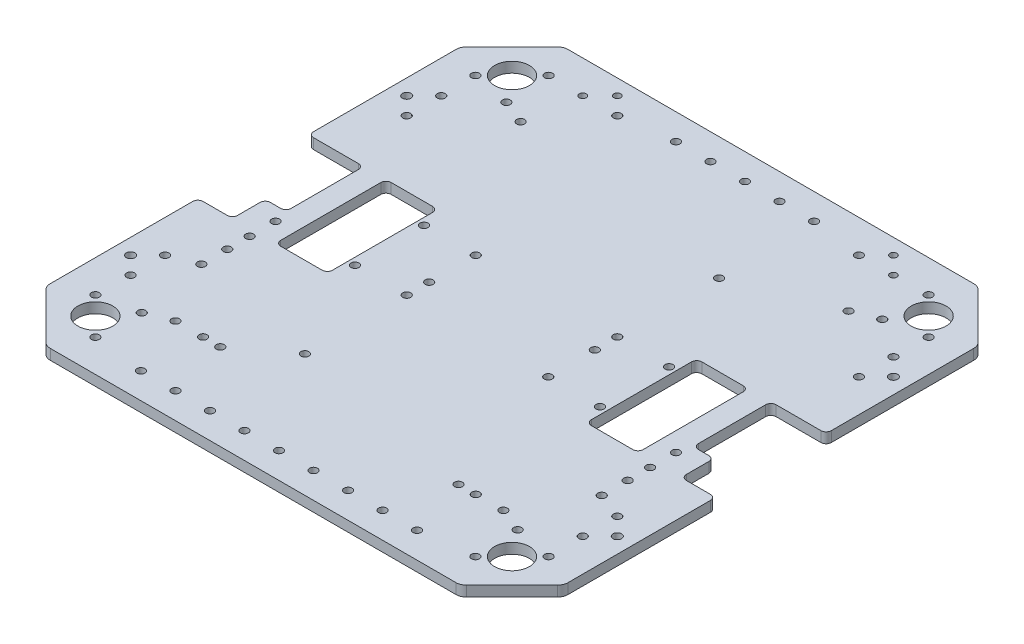
SolidWorks part; units mm, degrees
ref_plane "Plan de face" through (0, 0, 0) normal (0, 0, 1) x (1, 0, 0)
ref_plane "Plan de dessus" through (0, 0, 0) normal (0, 1, 0) x (1, 0, 0)
ref_plane "Plan de droite" through (0, 0, 0) normal (1, 0, 0) x (0, 0, -1)
sketch "Esquisse1" plane through (0, 0, 0) normal (0, 1, 0) x (1, 0, 0)
  line L0 (150, -150) -> (150, 150) construction
  line L1 (150, 150) -> (0, 150) construction
  line L2 (-150, 150) -> (-150, -150) construction
  line L3 (-150, 150) -> (150, 150) construction
  line L4 (150, 0) -> (-150, 0) construction
  line L5 (150, -150) -> (-150, -150) construction
  line L6 (0, 150) -> (0, -150) construction
  line L7 (-150, 0) -> (-150, 120)
  line L8 (0, 150) -> (-120, 150)
  line L9 (-150, 120) -> (-120, 150)
  line L10 (0, 150) -> (120, 150)
  line L11 (150, 0) -> (150, 120)
  line L12 (150, 120) -> (120, 150)
  line L13 (-150, 0) -> (-150, -120)
  line L14 (0, -150) -> (-120, -150)
  line L15 (-120, -150) -> (-150, -120)
  line L16 (150, 0) -> (150, -120)
  line L17 (0, -150) -> (120, -150)
  line L18 (120, -150) -> (150, -120)
  dimension "D1" = 42.4264
  dimension "D2" = 240
  dimension "D3" = 120
  dimension "D4" = 42.4264
  dimension "D5" = 120
  dimension "D6" = 300
  dimension "D7" = 300
  dimension "D8" = 30
extrude "Boss.-Extru.1" add sketch "Esquisse1" along normal blind 6
sketch "Esquisse2" plane through (0, 6, 0) normal (0, 1, 0) x (1, 0, 0)
  line L0 (-150, 0) -> (150, 0) construction
  line L1 (-150, 120) -> (-150, -120) construction
  line L2 (150, -120) -> (150, 120) construction
  line L3 (0, -150) -> (0, 150) construction
  line L4 (-120, -150) -> (120, -150) construction
  line L5 (120, 150) -> (-120, 150) construction
  line L6 (-150, 120) -> (-120, 150) construction
  line L7 (-120, 150) -> (-105.6975, 135.6975) construction
  line L8 (-105.6975, 135.6975) -> (-135.6975, 105.6975) construction
  line L9 (-135.6975, 105.6975) -> (-150, 120) construction
  line L10 (-120.6975, 120.6975) -> (-110.0909, 131.3041) construction
  line L11 (-120.6975, 120.6975) -> (-131.3041, 110.0909) construction
  line L12 (-135, -135) -> (135, 135) construction
  line L13 (-150, -120) -> (-120, -150) construction
  line L14 (150, 120) -> (120, 150) construction
  line L15 (-120.6975, 120.6975) -> (0, 120.6975) construction
  circle A0 centre (-120.6975, 120.6975) radius 10.1
  circle A1 centre (-131.3041, 110.0909) radius 2.3
  circle A2 centre (-110.0909, 131.3041) radius 2.3
extrude "Enlèv. mat.-Extru.1" cut sketch "Esquisse2" against normal up to next
mirror "Symétrie1" about plane through (0, 0, 0) normal (1, 0, 0) of "Enlèv. mat.-Extru.1"
mirror "Symétrie2" about plane through (0, 0, 0) normal (0, 0, 1) of "Symétrie1", "Enlèv. mat.-Extru.1"
sketch "Esquisse3" plane through (0, 6, 0) normal (0, 1, 0) x (1, 0, 0)
  line L0 (-150, 0) -> (150, 0) construction
  line L1 (-150, 120) -> (-150, -120) construction
  line L2 (150, -120) -> (150, 120) construction
  line L3 (0, -150) -> (0, 150) construction
  line L4 (-120, -150) -> (120, -150) construction
  line L5 (120, 150) -> (-120, 150) construction
  line L6 (-150, 0) -> (-150, -32)
  line L7 (-150, -32) -> (-130, -32)
  line L8 (-130, -32) -> (-130, 32)
  line L9 (-130, 32) -> (-150, 32)
  line L10 (-150, 32) -> (-150, 0)
extrude "Enlèv. mat.-Extru.2" cut sketch "Esquisse3" against normal up to next and the other way through all
mirror "Symétrie3" about plane through (0, 0, 0) normal (1, 0, 0) of "Enlèv. mat.-Extru.2"
fillet "Congé1" radius 3 8 edges at (-150, 3, 32) (-130, 3, 32) (-150, 3, -32) (-130, 3, -32) (150, 3, -32) (130, 3, -32) (150, 3, 32) (130, 3, 32)
sketch "Esquisse4" plane through (0, 6, 0) normal (0, 1, 0) x (1, 0, 0)
  line L0 (0, -150) -> (0, 150) construction
  line L1 (-120, -150) -> (120, -150) construction
  line L2 (120, 150) -> (-120, 150) construction
  line L3 (0, 150) -> (0, 0) construction
  line L4 (0, 0) -> (-130, 0) construction
  line L5 (-130, -29) -> (-130, 29) construction
  line L6 (-130, 0) -> (-105, 0) construction
  line L7 (-105, 0) -> (-105, 32)
  line L8 (-105, 32) -> (-75, 32)
  line L9 (-75, 32) -> (-75, -32)
  line L10 (-75, -32) -> (-105, -32)
  line L11 (-105, -32) -> (-105, 0)
extrude "Enlèv. mat.-Extru.3" cut sketch "Esquisse4" against normal up to next
mirror "Symétrie4" about plane through (0, 0, 0) normal (1, 0, 0) of "Enlèv. mat.-Extru.3"
fillet "Congé2" radius 3 8 edges at (105, 3, -32) (75, 3, -32) (105, 3, 32) (75, 3, 32) (-105, 3, 32) (-75, 3, 32) (-75, 3, -32) (-105, 3, -32)
sketch "Esquisse5" plane through (0, 6, 0) normal (0, 1, 0) x (1, 0, 0)
  line L0 (-75, 0) -> (-67, 0) construction
  line L1 (-75, -29) -> (-75, 29) construction
  line L2 (-67, 0) -> (-67, 24) construction
  line L3 (-67, 0) -> (-67, -24) construction
  line L4 (-67, -24) -> (-75, -24) construction
  line L5 (-75, -24) -> (-75, -16) construction
  line L6 (-75, -16) -> (-67, -24) construction
  line L7 (-67, -24) -> (-75, -24) construction
  line L9 (-67, 24) -> (-75, 24) construction
  line L10 (-75, 24) -> (-75, 16) construction
  line L11 (-75, 16) -> (-67, 24) construction
  line L12 (-67, 24) -> (-75, 24) construction
  circle A0 centre (-71, 20) radius 2.3
  circle A1 centre (-71, -20) radius 2.3
extrude "Enlèv. mat.-Extru.4" cut sketch "Esquisse5" against normal up to next
mirror "Symétrie5" about plane through (0, 0, 0) normal (1, 0, 0) of "Enlèv. mat.-Extru.4"
sketch "Esquisse6" plane through (0, 6, 0) normal (0, 1, 0) x (1, 0, 0)
  line L0 (-75, 0) -> (-75, 24) construction
  line L1 (-75, -29) -> (-75, 29) construction
  line L2 (-75, 24) -> (-67, 24) construction
  line L3 (-67, 24) -> (-45, 24) construction
  line L4 (-45, 24) -> (-37, 24) construction
  line L5 (-37, 24) -> (-37, -24) construction
  line L6 (-37, -24) -> (-45, -24) construction
  line L7 (-45, 24) -> (-45, 16) construction
  line L8 (-45, 16) -> (-37, 24) construction
  line L9 (-45, -24) -> (-45, -16) construction
  line L10 (-45, -16) -> (-37, -24) construction
  line L11 (-37, 24) -> (-37, -83) construction
  line L12 (-37, -83) -> (-45, -83) construction
  line L13 (-45, -83) -> (-45, -75) construction
  line L14 (-45, -75) -> (-37, -83) construction
  line L15 (75, 0) -> (67, 0) construction
  line L16 (75, -29) -> (75, 29) construction
  line L17 (75, 0) -> (75, -24) construction
  line L18 (75, -24) -> (67, -24) construction
  line L19 (67, 24) -> (75, 24) construction
  line L20 (75, 24) -> (75, 0) construction
  line L21 (67, -24) -> (45, -24) construction
  line L22 (45, -24) -> (45, -16) construction
  line L23 (67, -24) -> (67, 0) construction
  line L24 (45, -16) -> (37, -16) construction
  line L25 (37, -16) -> (37, -24) construction
  line L26 (37, -24) -> (45, -24) construction
  line L27 (45, -24) -> (37, -16) construction
  line L28 (37, -24) -> (37, 83) construction
  line L29 (37, 83) -> (45, 83) construction
  line L30 (45, 83) -> (45, 75) construction
  line L31 (45, 75) -> (37, 83) construction
  line L32 (37, 24) -> (45, 24) construction
  line L33 (45, 24) -> (45, 16) construction
  line L34 (45, 16) -> (37, 24) construction
  line L35 (37, -16) -> (37, 3) construction
  line L36 (37, 3) -> (45, 3) construction
  line L37 (45, 3) -> (45, 11) construction
  line L38 (45, 11) -> (37, 3) construction
  line L39 (-37, 24) -> (-37, -3) construction
  line L40 (-37, -3) -> (-45, -3) construction
  line L41 (-45, -3) -> (-45, -11) construction
  line L42 (-45, -11) -> (-37, -3) construction
  circle A0 centre (-41, -79) radius 2.3
  circle A1 centre (-41, -20) radius 2.3
  circle A2 centre (-41, 20) radius 2.3
  circle A3 centre (41, -20) radius 2.3
  circle A4 centre (41, 79) radius 2.3
  circle A5 centre (41, 20) radius 2.3
  circle A6 centre (41, 7) radius 2.3
  circle A7 centre (-41, -7) radius 2.3
extrude "Enlèv. mat.-Extru.5" cut sketch "Esquisse6" against normal up to next
sketch "Esquisse7" plane through (0, 6, 0) normal (0, 1, 0) x (1, 0, 0)
  line L1 (-3.3, 0) -> (3.3, 0) construction
  line L2 (150, -120) -> (150, -35) construction
  line L3 (120, -150) -> (150, -120) construction
  line L4 (131, 80) -> (131, 90) construction
  line L5 (131, 80) -> (131, 70) construction
  line L7 (150, -120) -> (150, -80) construction
  line L8 (150, -80) -> (146, -80) construction
  line L9 (146, -80) -> (141, -80) construction
  line L10 (141, -80) -> (131, -80) construction
  line L11 (131, -80) -> (131, -70) construction
  line L12 (131, -80) -> (131, -90) construction
  line L13 (141, 80) -> (131, 80) construction
  line L14 (146, 80) -> (141, 80) construction
  circle A9 centre (141, -80) radius 2.4769
  circle A10 centre (131, -90) radius 2.3
  circle A11 centre (131, -70) radius 2.3
  circle A12 centre (131, 70) radius 2.3
  circle A13 centre (131, 90) radius 2.3
  circle A14 centre (141, 80) radius 2.4769
  dimension "D1" = 40
  dimension "D2" = 4
  dimension "D3" = 5
extrude "Enlèv. mat.-Extru.6" cut sketch "Esquisse7" against normal up to next
mirror "Symétrie6" about plane through (0, 0, 0) normal (1, 0, 0) of "Enlèv. mat.-Extru.6"
sketch "Esquisse8" plane through (0, 6, 0) normal (0, 1, 0) x (1, 0, 0)
  line L0 (-60, -150) -> (-60, -135) construction
  line L1 (-40, -150) -> (-40, -135) construction
  line L2 (-20, -150) -> (-20, -135) construction
  line L3 (-120, -150) -> (-80, -150) construction
  line L4 (-80, -150) -> (-80, -135) construction
  line L5 (120, -150) -> (80, -150) construction
  line L6 (80, -150) -> (80, -135) construction
  line L7 (0, -150) -> (0, -135) construction
  line L8 (20, -150) -> (20, -135) construction
  line L9 (40, -150) -> (40, -135) construction
  line L10 (60, -150) -> (60, -135) construction
  line L11 (-3.3, 0) -> (3.3, 0) construction
  line L13 (40, 150) -> (40, 135) construction
  line L14 (20, 150) -> (20, 135) construction
  line L15 (0, 150) -> (0, 135) construction
  line L19 (-120, 150) -> (-80, 150) construction
  line L20 (-20, 150) -> (-20, 135) construction
  line L21 (-40, 150) -> (-40, 135) construction
  circle A0 centre (-80, -135) radius 2.3
  circle A1 centre (80, -135) radius 2.3
  circle A2 centre (-60, -135) radius 2.3
  circle A3 centre (-40, -135) radius 2.3
  circle A4 centre (-20, -135) radius 2.3
  circle A5 centre (0, -135) radius 2.3
  circle A6 centre (20, -135) radius 2.3
  circle A7 centre (40, -135) radius 2.3
  circle A8 centre (60, -135) radius 2.3
  circle A10 centre (40, 135) radius 2.3
  circle A11 centre (20, 135) radius 2.3
  circle A12 centre (0, 135) radius 2.3
  circle A13 centre (-20, 135) radius 2.3
  circle A14 centre (-40, 135) radius 2.3
  dimension "D1" = 8
extrude "Enlèv. mat.-Extru.7" cut sketch "Esquisse8" against normal up to next
sketch "Esquisse10" plane through (0, 6, 0) normal (0, 1, 0) x (1, 0, 0)
  line L0 (-150, -120) -> (-150, -32) construction
  line L1 (-150, -32) -> (-120, -32) construction
  line L2 (-120, -32) -> (-112, -32) construction
  line L3 (-112, -32) -> (-112, -40) construction
  line L4 (-112, -40) -> (-120, -40) construction
  line L5 (-120, -40) -> (-120, -60) construction
  line L6 (-120, -60) -> (-112, -60) construction
  line L7 (-112, -60) -> (-112, -68) construction
  line L8 (-112, -68) -> (-120, -60) construction
  line L9 (-120, -32) -> (-112, -40) construction
  circle A0 centre (-116, -36) radius 2.3
  circle A1 centre (-116, -64) radius 2.3
extrude "Enlèv. mat.-Extru.8" cut sketch "Esquisse10" against normal up to next
mirror "Symétrie8" about plane through (0, 0, 0) normal (1, 0, 0) of "Enlèv. mat.-Extru.8"
fillet "Congé3" radius 6 8 edges at (150, 3, -120) (120, 3, -150) (-120, 3, -150) (-150, 3, -120) (-150, 3, 120) (-120, 3, 150) (120, 3, 150) (150, 3, 120)
sketch "Esquisse11" plane through (0, 6, 0) normal (0, 1, 0) x (1, 0, 0)
  line L0 (150, 0) -> (-150, 0) construction
  line L1 (-150, 0) -> (-150, -32) construction
  line L2 (-150, -32) -> (-120, -32) construction
  line L3 (-120, -32) -> (-120, -25) construction
  line L4 (-120, -25) -> (-120, -17) construction
  line L5 (-120, -17) -> (-112, -17) construction
  line L6 (-112, -17) -> (-112, -25) construction
  line L7 (-112, -25) -> (-112, -45) construction
  line L8 (-112, -45) -> (-112, -53) construction
  line L9 (-112, -53) -> (-120, -53) construction
  line L10 (-120, -53) -> (-120, -32) construction
  line L11 (-112, -45) -> (-120, -45) construction
  line L12 (-120, -45) -> (-112, -53) construction
  line L13 (-120, -25) -> (-112, -17) construction
  line L14 (0, -3.3) -> (0, 3.3) construction
  line L15 (120, -25) -> (112, -17) construction
  line L16 (120, -45) -> (112, -53) construction
  line L17 (112, -45) -> (120, -45) construction
  line L18 (120, -53) -> (120, -32) construction
  line L19 (112, -53) -> (120, -53) construction
  line L20 (112, -45) -> (112, -53) construction
  line L21 (112, -25) -> (112, -45) construction
  line L22 (112, -17) -> (112, -25) construction
  line L23 (120, -17) -> (112, -17) construction
  line L24 (120, -25) -> (120, -17) construction
  line L25 (120, -32) -> (120, -25) construction
  line L26 (150, -32) -> (120, -32) construction
  line L27 (150, 0) -> (150, -32) construction
  circle A0 centre (-116, -21) radius 2.3
  circle A1 centre (-116, -49) radius 2.3
  circle A2 centre (116, -49) radius 2.3
  circle A3 centre (116, -21) radius 2.3
  point P30 (0, 0)
extrude "Enlèv. mat.-Extru.9" cut sketch "Esquisse11" against normal up to next
sketch "Esquisse12" plane through (0, 6, 0) normal (0, 1, 0) x (1, 0, 0)
  line L0 (0, -3.3) -> (0, 3.3) construction
  line L1 (-108.9078, -105.6191) -> (-97.0876, -114.854) construction
  line L2 (-97.0876, -114.854) -> (-95, -100) construction
  line L3 (95, -100) -> (95, -150) construction
  line L4 (97.0876, -114.854) -> (95, -100) construction
  line L5 (108.9078, -105.6191) -> (97.0876, -114.854) construction
  line L6 (-95, -100) -> (-95, -150) construction
  line L7 (-117.5147, -150) -> (117.5147, -150) construction
  circle A2 centre (-95, -100) radius 2.3
  circle A5 centre (-108.9078, -105.6191) radius 2.3
  circle A15 centre (108.9078, -105.6191) radius 2.3
  circle A16 centre (95, -100) radius 2.3
  point P7 (0, -150)
  dimension "D1" = 95
  dimension "D6" = 60
  dimension "D2" = 50
  dimension "D3" = 15
  dimension "D4" = 50
  dimension "D5" = 15
  dimension "D7" = 8
extrude "Enlèv. mat.-Extru.10" cut sketch "Esquisse12" against normal up to next
mirror "Symétrie9" about plane through (0, 0, 0) normal (0, 0, 1) of "Enlèv. mat.-Extru.10"
sketch "Esquisse13" plane through (0, 6, 0) normal (0, 1, 0) x (1, 0, 0)
  line L0 (74, -150) -> (-74, -150) construction
  line L1 (-117.5147, -150) -> (117.5147, -150) construction
  line L2 (-74, -150) -> (-74, -100) construction
  line L3 (-74, -100) -> (-69, -100) construction
  line L4 (-74, -100) -> (-79, -100) construction
  line L5 (0, -3.3) -> (0, 3.3) construction
  line L6 (74, -100) -> (79, -100) construction
  line L7 (74, -100) -> (69, -100) construction
  line L8 (74, -150) -> (74, -100) construction
  circle A0 centre (-79, -100) radius 2.3
  circle A1 centre (-69, -100) radius 2.3
  circle A2 centre (69, -100) radius 2.3
  circle A3 centre (79, -100) radius 2.3
  point P15 (0, -150)
  dimension "D1" = 74
  dimension "D2" = 50
  dimension "D3" = 5
  dimension "D4" = 5
extrude "Enlèv. mat.-Extru.11" cut sketch "Esquisse13" against normal up to next
sketch "Esquisse14" plane through (0, 6, 0) normal (0, 1, 0) x (1, 0, 0)
  line L0 (0, 150) -> (80, 150) construction
  line L1 (117.5147, 150) -> (-117.5147, 150) construction
  line L2 (80, 150) -> (80, 131) construction
  line L3 (80, 131) -> (70, 131) construction
  line L4 (80, 131) -> (90, 131) construction
  line L5 (80, 150) -> (80, 141) construction
  circle A0 centre (70, 131) radius 2.3
  circle A1 centre (90, 131) radius 2
  circle A2 centre (80, 141) radius 2
  dimension "D2" = 19
  dimension "D4" = 10
  dimension "D1" = 80
  dimension "D3" = 10
  dimension "D5" = 9
extrude "Enlèv. mat.-Extru.12" cut sketch "Esquisse14" against normal up to next
mirror "Symétrie10" about plane through (0, 0, 0) normal (1, 0, 0) of "Enlèv. mat.-Extru.12"
sketch "Esquisse15" plane through (0, 6, 0) normal (0, 1, 0) x (1, 0, 0)
  line L0 (-90, 32) -> (-150, 32) construction
  line L1 (-78, 32) -> (-102, 32) construction
  line L2 (-150, 32) -> (-150, 35) construction
  line L3 (-150, 32) -> (-150, -13) construction
  line L4 (-150, -13) -> (-133, -13) construction
  line L5 (-133, -13) -> (-118, -13)
  line L6 (-118, -13) -> (-118, 32)
  line L7 (-133, -13) -> (-133, 32)
  line L8 (-133, 32) -> (-118, 32)
  dimension "D1" = 17
  dimension "D2" = 45
extrude "Enlèv. mat.-Extru.13" cut sketch "Esquisse15" against normal up to next
mirror "Symétrie11" about plane through (0, 0, 0) normal (1, 0, 0) of "Enlèv. mat.-Extru.13"
fillet "Congé4" radius 3 6 edges at (-118, 3, 13) (-130, 3, 13) (-118, 3, -32) (118, 3, -32) (118, 3, 13) (130, 3, 13)
